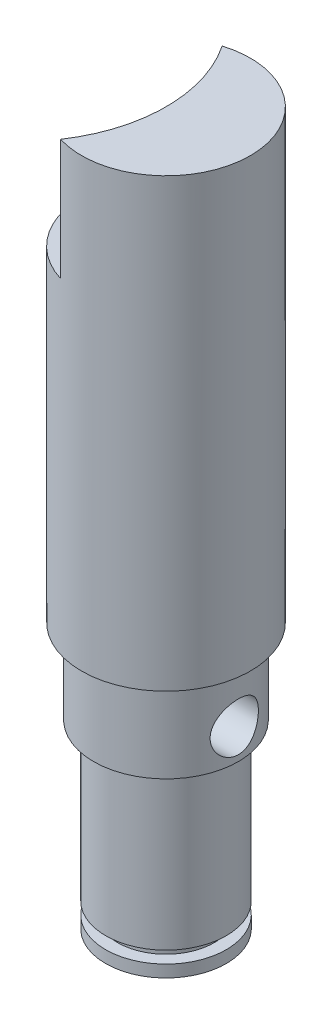
SolidWorks part; units mm, degrees
ref_plane "Front Plane" through (0, 0, 0) normal (0, 0, 1) x (1, 0, 0)
ref_plane "Top Plane" through (0, 0, 0) normal (0, 1, 0) x (1, 0, 0)
ref_plane "Right Plane" through (0, 0, 0) normal (1, 0, 0) x (0, 0, -1)
sketch "Sketch1" plane through (0, 0, 0) normal (0, 1, 0) x (1, 0, 0)
  circle A0 centre (0, 0) radius 2.5
  dimension "D1" = 5
extrude "Boss-Extrude1" add sketch "Sketch1" along normal blind 0.5
sketch "Sketch2" plane through (0, 0.5, 0) normal (0, 1, 0) x (1, 0, 0)
  circle A0 centre (0, 0) radius 2
  dimension "D1" = 4
extrude "Boss-Extrude2" add sketch "Sketch2" along normal blind 0.5
sketch "Sketch3" plane through (0, 1, 0) normal (0, 1, 0) x (1, 0, 0)
  circle A0 centre (0, 0) radius 2.5 construction
  circle A1 centre (0, 0) radius 2.5
  dimension "D1" = 5
extrude "Boss-Extrude3" add sketch "Sketch3" along normal blind 6.5
sketch "Sketch4" plane through (0, 7.5, 0) normal (0, 1, 0) x (1, 0, 0)
  circle A0 centre (0, 0) radius 3
  dimension "D1" = 6
extrude "Boss-Extrude4" add sketch "Sketch4" along normal blind 3.5
sketch "Sketch5" plane through (0, 11, 0) normal (0, 1, 0) x (1, 0, 0)
  circle A2 centre (0, 0) radius 3.5
  circle A3 centre (0, 0) radius 3.5
  dimension "D1" = 0.5
extrude "Boss-Extrude5" add sketch "Sketch5" along normal blind 18.5
sketch "Sketch8" plane through (0, 0, 0) normal (0, 1, 0) x (1, 0, 0)
  line L0 (0, 3.4329) -> (0, -3.5) construction
  arc A0 (-1.0208, 3.3478) -> (-1.0208, -3.3478) centre (-6, 0) cw
  circle A1 centre (0, 0) radius 3.5 construction
  arc A2 (-1.0208, 3.3478) -> (-1.0208, -3.3478) centre (0, 0) ccw
  dimension "D1" = 6
extrude "Cut-Extrude2" cut sketch "Sketch8" against normal blind 5 from surface at 29.5 starting at face at (0, 29.5, 3.5)
sketch "Sketch10" plane through (0, 0, 0) normal (1, 0, 0) x (0, 0, -1)
  line L0 (-3, 11) -> (3, 11) construction
  circle A0 centre (0, 8.75) radius 1
  point P4 (0, 0)
  dimension "D2" = 2
  dimension "D1" = 2.25
extrude "Cut-Extrude3" cut sketch "Sketch10" against normal through all both and the other way through all
